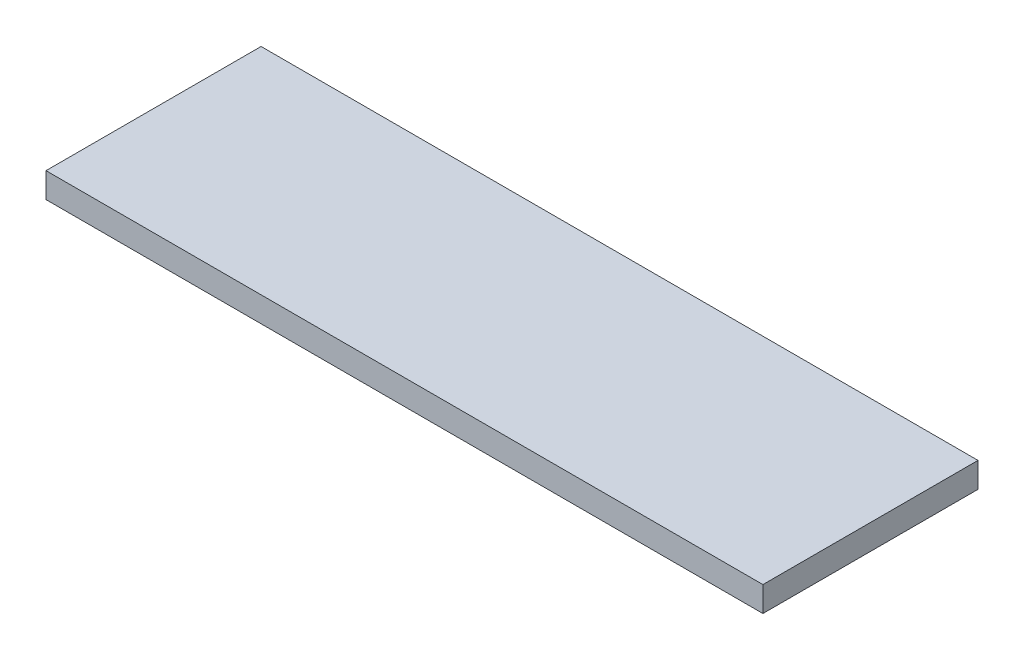
SolidWorks part; units mm, degrees
material "Rubber"
ref_plane "Front Plane" through (0, 0, 0) normal (0, 0, 1) x (1, 0, 0)
ref_plane "Top Plane" through (0, 0, 0) normal (0, 1, 0) x (1, 0, 0)
ref_plane "Right Plane" through (0, 0, 0) normal (1, 0, 0) x (0, 0, -1)
sketch "Sketch1" plane through (0, 0, 0) normal (0, 1, 0) x (1, 0, 0)
  line L1 (-63.5, -19.05) -> (63.5, -19.05)
  line L2 (-63.5, -19.05) -> (-63.5, 19.05)
  line L3 (-63.5, 19.05) -> (63.5, 19.05)
  line L4 (63.5, -19.05) -> (63.5, 19.05)
  line L5 (-63.5, -19.05) -> (63.5, 19.05) construction
  line L6 (-63.5, 19.05) -> (63.5, -19.05) construction
  point P0 (0, 0)
  dimension "D1" = 127
  dimension "D2" = 38.1
extrude "Boss-Extrude1" add sketch "Sketch1" along normal mid plane 4.445
